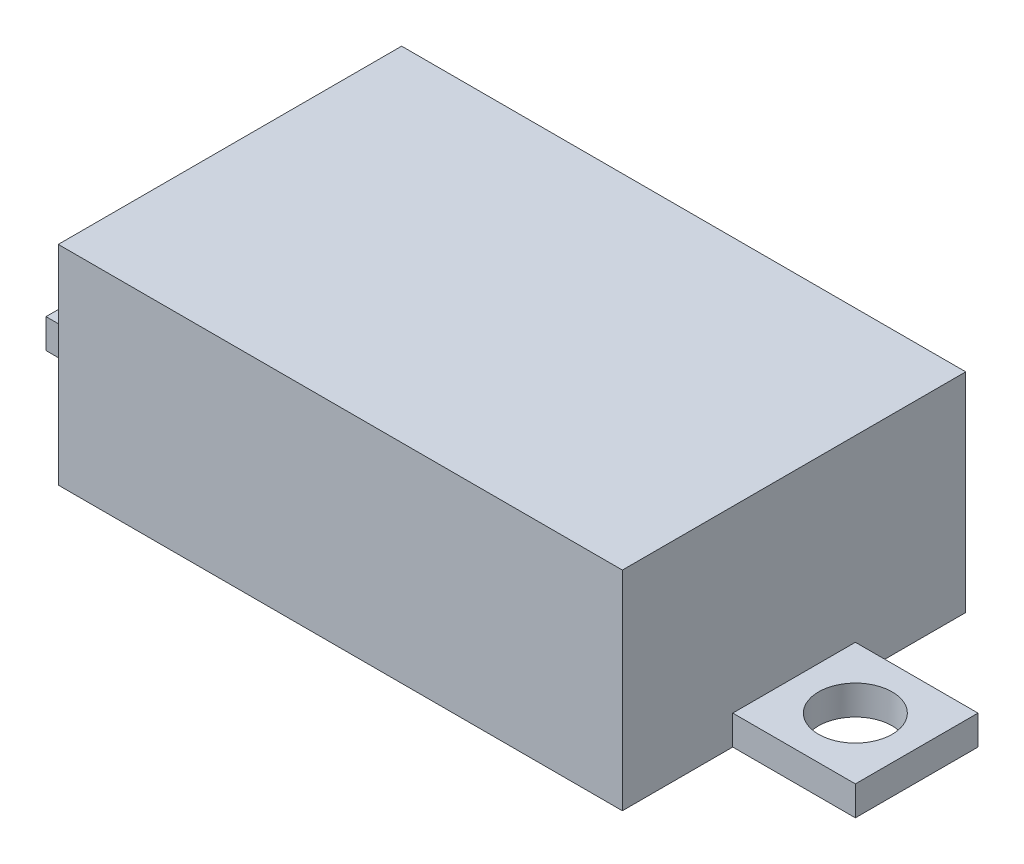
SolidWorks part; units mm, degrees
ref_plane "Front Plane" through (0, 0, 0) normal (0, 0, 1) x (1, 0, 0)
ref_plane "Top Plane" through (0, 0, 0) normal (0, 1, 0) x (1, 0, 0)
ref_plane "Right Plane" through (0, 0, 0) normal (1, 0, 0) x (0, 0, -1)
sketch "Sketch1" plane through (0, 0, 0) normal (0, 1, 0) x (1, 0, 0)
  line L1 (0, 0) -> (23, 0)
  line L2 (0, 0) -> (0, 14)
  line L3 (0, 14) -> (23, 14)
  line L4 (23, 0) -> (23, 14)
  dimension "D1" = 23
  dimension "D2" = 14
extrude "Boss-Extrude1" add sketch "Sketch1" along normal blind 8.5
sketch "Sketch2" plane through (0, 0, 0) normal (0, -1, 0) x (1, 0, 0)
  line L0 (0, 0) -> (23, 0) construction
  line L1 (-5, -4.5) -> (28, -4.5)
  line L2 (-5, -4.5) -> (-5, -9.5)
  line L3 (-5, -9.5) -> (28, -9.5)
  line L4 (28, -4.5) -> (28, -9.5)
  line L5 (23, 0) -> (23, -14) construction
  point P4 (11.5, -4.5)
  point P7 (11.5, 0)
  point P8 (28, -7)
  point P11 (23, -7)
  dimension "D1" = 5
  dimension "D2" = 33
extrude "Boss-Extrude2" add sketch "Sketch2" against normal blind 1.2
sketch "Sketch3" plane through (0, 1.2, 0) normal (0, 1, 0) x (1, 0, 0)
  line L1 (28, 9.5) -> (28, 4.5) construction
  line L2 (23, 9.5) -> (28, 9.5) construction
  line L3 (-5, 9.5) -> (0, 9.5) construction
  circle A0 centre (-2.5, 7) radius 1.5
  circle A1 centre (25.5, 7) radius 1.5
  point P6 (28, 7)
  point P7 (0, 0)
  point P10 (25.5, 9.5)
  point P13 (-2.5, 9.5)
  dimension "D1" = 3
extrude "Cut-Extrude1" cut sketch "Sketch3" against normal blind 10
